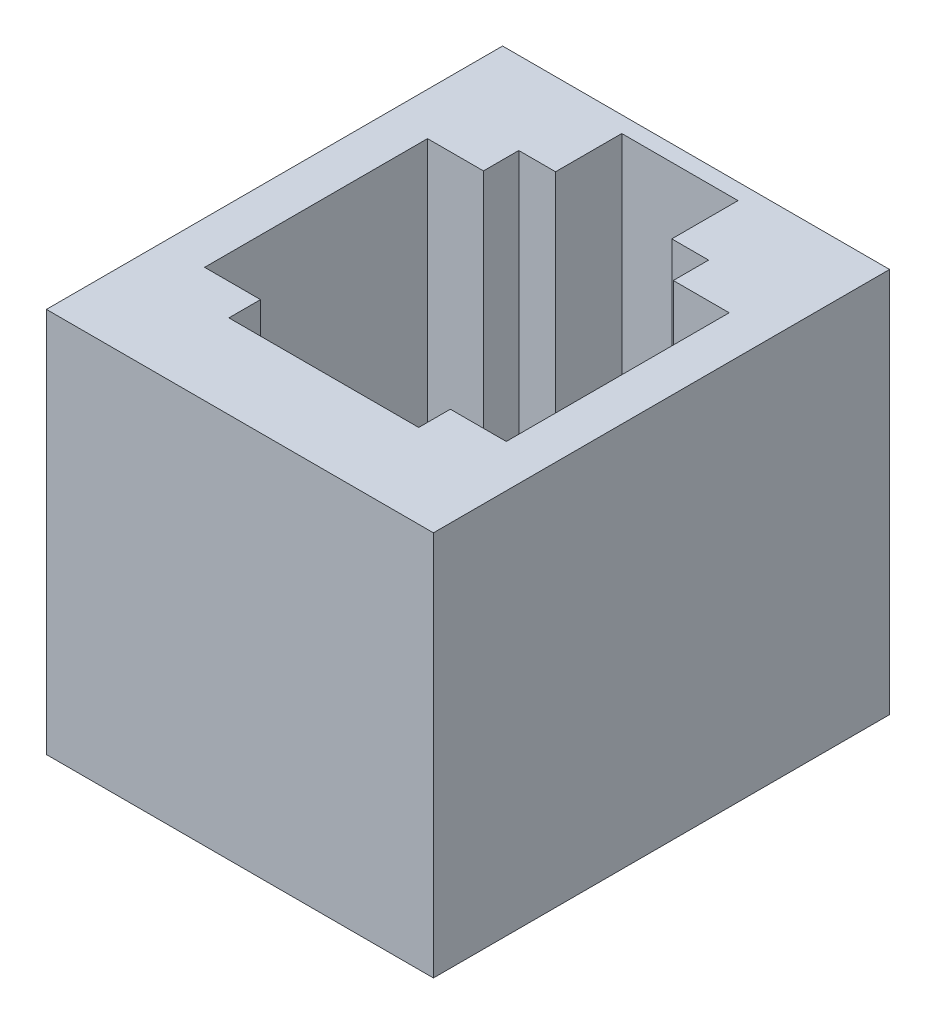
SolidWorks part; units mm, degrees
ref_plane "Front Plane" through (0, 0, 0) normal (0, 0, 1) x (1, 0, 0)
ref_plane "Top Plane" through (0, 0, 0) normal (0, 1, 0) x (1, 0, 0)
ref_plane "Right Plane" through (0, 0, 0) normal (1, 0, 0) x (0, 0, -1)
sketch "Sketch1" plane through (0, 0, 0) normal (0, 1, 0) x (1, 0, 0)
  line L1 (-6.6802, -7.874) -> (6.6802, -7.874)
  line L2 (-6.6802, -7.874) -> (-6.6802, 7.874)
  line L3 (-6.6802, 7.874) -> (6.6802, 7.874)
  line L4 (6.6802, -7.874) -> (6.6802, 7.874)
  line L5 (-6.6802, -7.874) -> (6.6802, 7.874) construction
  line L6 (-6.6802, 7.874) -> (6.6802, -7.874) construction
  point P0 (0, 0)
  dimension "D1" = 13.3604
  dimension "D2" = 15.748
extrude "Boss-Extrude1" add sketch "Sketch1" along normal blind 13.3096
sketch "Sketch2" plane through (0, 13.3096, 0) normal (0, 1, 0) x (1, 0, 0)
  line L0 (-2.0066, 7.3152) -> (-2.0066, 5.0292)
  line L1 (-2.0066, 5.0292) -> (-3.2766, 5.0292)
  line L2 (-3.2766, 5.0292) -> (-3.2766, 3.81)
  line L3 (-3.2766, 3.81) -> (-5.207, 3.81)
  line L4 (-5.207, 3.81) -> (-5.207, -3.8862)
  line L5 (-5.207, -3.8862) -> (-3.2766, -3.8862)
  line L6 (-3.2766, -3.8862) -> (-3.2766, -4.9784)
  line L7 (-3.2766, -4.9784) -> (3.2766, -4.9784)
  line L8 (3.2766, -4.9784) -> (3.2766, -3.8862)
  line L9 (3.2766, -3.8862) -> (5.207, -3.8862)
  line L10 (5.207, -3.8862) -> (5.207, 3.81)
  line L11 (5.207, 3.81) -> (3.2766, 3.81)
  line L12 (3.2766, 3.81) -> (3.2766, 5.0292)
  line L13 (3.2766, 5.0292) -> (2.0066, 5.0292)
  line L14 (2.0066, 5.0292) -> (2.0066, 7.3152)
  line L15 (2.0066, 7.3152) -> (-2.0066, 7.3152)
  line L16 (5.207, -0.0381) -> (6.6802, -0.0381) construction
  line L17 (6.6802, -7.874) -> (6.6802, 7.874) construction
  line L18 (-5.207, -0.0381) -> (-6.6802, -0.0381) construction
  line L19 (-6.6802, 7.874) -> (-6.6802, -7.874) construction
  line L20 (6.6802, 7.874) -> (-6.6802, 7.874) construction
  line L21 (-6.6802, -7.874) -> (6.6802, -7.874) construction
  dimension "D1" = 0.5588
  dimension "D2" = 1.4732
  dimension "D3" = 2.8956
  dimension "D4" = 1.2192
  dimension "D5" = 1.27
  dimension "D6" = 1.0922
  dimension "D7" = 1.9304
  dimension "D8" = 2.286
  dimension "D9" = 1.9304
extrude "Cut-Extrude1" cut sketch "Sketch2" against normal blind 6.731
sketch "Sketch3" plane through (0, 6.5786, 0) normal (0, 1, 0) x (1, 0, 0)
  line L0 (-3.2766, -3.8862) -> (3.2766, -3.8862)
  line L16 (2.0066, 7.3152) -> (-2.0066, 7.3152)
  line L17 (-2.0066, 7.3152) -> (-2.0066, 5.0292)
  line L18 (-2.0066, 5.0292) -> (-3.2766, 5.0292)
  line L19 (-3.2766, 5.0292) -> (-3.2766, 3.81)
  line L20 (-3.2766, 3.81) -> (-5.207, 3.81)
  line L21 (-5.207, 3.81) -> (-5.207, -3.8862)
  line L22 (-5.207, -3.8862) -> (-3.2766, -3.8862)
  line L23 (-3.2766, -3.8862) -> (-3.2766, -4.9784)
  line L24 (-3.2766, -4.9784) -> (3.2766, -4.9784)
  line L25 (3.2766, -4.9784) -> (3.2766, -3.8862)
  line L26 (3.2766, -3.8862) -> (5.207, -3.8862)
  line L27 (5.207, -3.8862) -> (5.207, 3.81)
  line L28 (5.207, 3.81) -> (3.2766, 3.81)
  line L29 (3.2766, 3.81) -> (3.2766, 5.0292)
  line L30 (3.2766, 5.0292) -> (2.0066, 5.0292)
  line L31 (2.0066, 5.0292) -> (2.0066, 7.3152)
  line L32 (2.0066, 7.3152) -> (-2.0066, 7.3152)
  line L33 (-2.0066, 7.3152) -> (-2.0066, 5.0292)
  line L34 (-2.0066, 5.0292) -> (-3.2766, 5.0292)
  line L35 (-3.2766, 5.0292) -> (-3.2766, 3.81)
  line L36 (-3.2766, 3.81) -> (-5.207, 3.81)
  line L37 (-5.207, 3.81) -> (-5.207, -3.8862)
  line L38 (-5.207, -3.8862) -> (-3.2766, -3.8862)
  line L42 (3.2766, -3.8862) -> (5.207, -3.8862)
  line L43 (5.207, -3.8862) -> (5.207, 3.81)
  line L44 (5.207, 3.81) -> (3.2766, 3.81)
  line L45 (3.2766, 3.81) -> (3.2766, 5.0292)
  line L46 (3.2766, 5.0292) -> (2.0066, 5.0292)
  line L47 (2.0066, 5.0292) -> (2.0066, 7.3152)
  dimension "D1" = 0
extrude "Cut-Extrude2" cut sketch "Sketch3" against normal blind 6.4516
sketch "Sketch4" plane through (0, 6.5786, 0) normal (0, 1, 0) x (1, 0, 0)
  line L0 (-3.2766, -3.8862) -> (3.2766, -3.8862) construction
  line L1 (-1.0795, -3.8862) -> (-0.8255, -3.8862)
  line L2 (-1.0795, -3.8862) -> (-1.0795, -4.9784)
  line L3 (-1.0795, -4.9784) -> (-0.8255, -4.9784)
  line L4 (-0.8255, -3.8862) -> (-0.8255, -4.9784)
  line L5 (-3.2766, -4.9784) -> (3.2766, -4.9784) construction
  line L6 (-0.1905, -3.8862) -> (0.1905, -3.8862) construction
  line L7 (-0.4445, -4.9784) -> (-0.1905, -4.9784)
  line L8 (-0.4445, -4.9784) -> (-0.4445, -3.8862)
  line L9 (-0.4445, -3.8862) -> (-0.1905, -3.8862)
  line L10 (-0.1905, -4.9784) -> (-0.1905, -3.8862)
  line L11 (0.1905, -3.8862) -> (0.4445, -3.8862)
  line L12 (0.1905, -3.8862) -> (0.1905, -4.9784)
  line L13 (0.1905, -4.9784) -> (0.4445, -4.9784)
  line L14 (0.4445, -3.8862) -> (0.4445, -4.9784)
  line L15 (0.8255, -4.9784) -> (1.0795, -4.9784)
  line L16 (0.8255, -4.9784) -> (0.8255, -3.8862)
  line L17 (0.8255, -3.8862) -> (1.0795, -3.8862)
  line L18 (1.0795, -4.9784) -> (1.0795, -3.8862)
  line L19 (0.4445, -3.8862) -> (0.8255, -3.8862) construction
  line L20 (-0.4445, -3.8862) -> (-0.8255, -3.8862) construction
  point P20 (0, -3.8862)
  dimension "D1" = 0.381
  dimension "D2" = 0.254
extrude "Cut-Extrude3" cut sketch "Sketch4" against normal up to surface (6.4516 mm away) up to face at (0, 0.127, -3.5179)
ref_plane "Plane1" through (0, 1.7889, 0.6939) normal (0, -0.9323, -0.3616) x (-1, 0, 0)
sketch "Sketch5" plane through (0, 1.7889, 0.6939) normal (0, -0.9323, -0.3616) x (-1, 0, 0)
  line L0 (0.8255, -4.5956) -> (1.0795, -4.5956) construction
  line L1 (1.0795, -4.5956) -> (0.8255, -4.5956)
  line L2 (1.0795, -4.5956) -> (1.0795, -2.3895)
  line L3 (1.0795, -2.3895) -> (0.8255, -2.3895) construction
  line L4 (0.8255, -4.5956) -> (0.8255, -2.3895)
  line L5 (3.2766, -2.2625) -> (1.0795, -2.2625) construction
  line L6 (0.4445, -4.5956) -> (0.1905, -4.5956)
  line L7 (0.4445, -4.5956) -> (0.4445, -2.3895)
  line L8 (0.4445, -2.3895) -> (0.1905, -2.3895) construction
  line L9 (0.1905, -4.5956) -> (0.1905, -2.3895)
  line L10 (-0.1905, -4.5956) -> (-0.4445, -4.5956)
  line L11 (-0.1905, -4.5956) -> (-0.1905, -2.3895)
  line L12 (-0.1905, -2.3895) -> (-0.4445, -2.3895) construction
  line L13 (-0.4445, -4.5956) -> (-0.4445, -2.3895)
  line L14 (-0.8255, -4.5956) -> (-1.0795, -4.5956)
  line L15 (-0.8255, -4.5956) -> (-0.8255, -2.3895)
  line L16 (-0.8255, -2.3895) -> (-1.0795, -2.3895) construction
  line L17 (-1.0795, -4.5956) -> (-1.0795, -2.3895)
  line L18 (3.2766, -2.2625) -> (1.0795, -2.2625) construction
  arc A0 (1.0795, -2.3895) -> (0.8255, -2.3895) centre (0.9525, -2.3895) ccw
  arc A1 (0.4445, -2.3895) -> (0.1905, -2.3895) centre (0.3175, -2.3895) ccw
  arc A2 (-0.1905, -2.3895) -> (-0.4445, -2.3895) centre (-0.3175, -2.3895) ccw
  arc A3 (-0.8255, -2.3895) -> (-1.0795, -2.3895) centre (-0.9525, -2.3895) ccw
extrude "Boss-Extrude2" add sketch "Sketch5" along normal up to next and the other way up to next
sketch "Sketch6" plane through (0, 0, 0) normal (0, -1, 0) x (1, 0, 0)
  line L1 (-1.0795, 2.54) -> (-0.8255, 2.54)
  line L2 (-1.0795, 2.54) -> (-1.0795, -3.5052)
  line L3 (-1.0795, -3.5052) -> (-0.8255, -3.5052)
  line L4 (-0.8255, 2.54) -> (-0.8255, -3.5052)
  line L5 (-0.4445, 2.54) -> (-0.1905, 2.54)
  line L6 (-0.4445, 2.54) -> (-0.4445, -3.5052)
  line L7 (-0.4445, -3.5052) -> (-0.1905, -3.5052)
  line L8 (-0.1905, 2.54) -> (-0.1905, -3.5052)
  line L9 (0.8255, 2.54) -> (1.0795, 2.54)
  line L10 (0.8255, 2.54) -> (0.8255, -3.5052)
  line L11 (0.8255, -3.5052) -> (1.0795, -3.5052)
  line L12 (1.0795, 2.54) -> (1.0795, -3.5052)
  line L13 (0.1905, 2.54) -> (0.4445, 2.54)
  line L14 (0.1905, 2.54) -> (0.1905, -3.5052)
  line L15 (0.1905, -3.5052) -> (0.4445, -3.5052)
  line L16 (0.4445, 2.54) -> (0.4445, -3.5052)
  line L17 (-1.0795, 2.6122) -> (-1.0795, 3.8862) construction
  line L18 (-0.8255, 3.8862) -> (-0.8255, 2.6122) construction
  line L19 (-0.4445, 2.6122) -> (-0.4445, 3.8862) construction
  line L20 (0.1905, 2.6122) -> (0.1905, 3.8862) construction
  line L21 (0.8255, 3.8862) -> (0.8255, 2.6122) construction
  line L22 (2.0066, -7.3152) -> (-2.0066, -7.3152) construction
  dimension "D1" = 3.81
  dimension "D2" = 6.0452
extrude "Cut-Extrude4" cut sketch "Sketch6" against normal up to next
